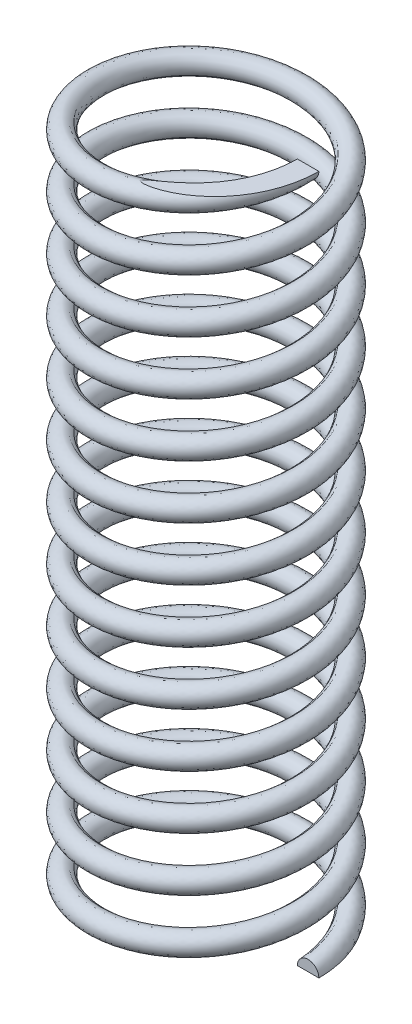
SolidWorks part; units mm, degrees
ref_plane "Front Plane" through (0, 0, 0) normal (0, 0, 1) x (1, 0, 0)
ref_plane "Top Plane" through (0, 0, 0) normal (0, 1, 0) x (1, 0, 0)
ref_plane "Right Plane" through (0, 0, 0) normal (1, 0, 0) x (0, 0, -1)
sketch "Sketch1" plane through (0, 0, 0) normal (0, 1, 0) x (1, 0, 0)
  circle A0 centre (0, 0) radius 19
  dimension "D1" = 38
curve "Helix/Spiral1" pitch 10 height 130 turns 13
sketch "Sketch2" plane through (0, 0, 0) normal (0, 0, 1) x (1, 0, 0)
  line L0 (0, 0) -> (19, 0) construction
  circle A0 centre (19, 0) radius 2
  spline S0 degree 3 poles (19, 0) (19, 0.1719) (18.3234, 0.5183) (15.385, 1.0358) (10.8317, 1.5538) (5.1414, 2.0717) (-1.0886, 2.5896) (-7.2043, 3.1076) (-12.5638, 3.6255) (-16.6045, 4.1434) (-18.9022, 4.6614) (-19.2158, 5.1793) (-17.5122, 5.6972) (-13.9705, 6.2151) (-8.9622, 6.7331) (-3.0132, 7.251) (3.2521, 7.7689) (9.176, 8.2869) (14.1367, 8.8048) (17.6135, 9.3227) (19.2415, 9.8406) (18.8496, 10.3586) (16.4791, 10.8765) (12.3789, 11.3944) (6.9792, 11.9124) (0.8469, 12.4303) (-5.3743, 12.9482) (-11.0313, 13.4661) (-15.5304, 13.9841) (-18.3993, 14.502) (-19.3368, 15.0199) (-18.2445, 15.5378) (-15.2371, 16.0558) (-10.6303, 16.5737) (-4.9076, 17.0916) (1.3302, 17.6096) (7.4284, 18.1275) (12.7469, 18.6454) (16.7273, 19.1633) (18.9518, 19.6813) (19.187, 20.1992) (17.4082, 20.7171) (13.802, 21.2351) (8.747, 21.753) (2.7739, 22.2709) (-3.4904, 22.7888) (-9.3883, 23.3068) (-14.3008, 23.8247) (-17.7121, 24.3426) (-19.2641, 24.8606) (-18.7941, 25.3785) (-16.3512, 25.8964) (-12.1919, 26.4143) (-6.7529, 26.9323) (-0.605, 27.4502) (5.6064, 27.9681) (11.2293, 28.4861) (15.6734, 29.004) (18.4724, 29.5219) (19.3323, 30.0398) (18.1629, 30.5578) (15.0869, 31.0757) (10.4273, 31.5936) (4.6731, 32.1116) (-1.5716, 32.6295) (-7.6513, 33.1474) (-12.9279, 33.6653) (-16.8474, 34.1833) (-18.9985, 34.7012) (-19.1553, 35.2191) (-17.3014, 35.7371) (-13.6314, 36.255) (-8.5305, 36.7729) (-2.5342, 37.2908) (3.7282, 37.8088) (9.5992, 38.3267) (14.4626, 38.8446) (17.8078, 39.3625) (19.2838, 39.8805) (18.7356, 40.3984) (16.2207, 40.9163) (12.0031, 41.4343) (6.5256, 41.9522) (0.363, 42.4701) (-5.8376, 42.988) (-11.4254, 43.506) (-15.814, 44.0239) (-18.5425, 44.5418) (-19.3247, 45.0598) (-18.0783, 45.5777) (-14.9343, 46.0956) (-10.2226, 46.6135) (-4.4379, 47.1315) (1.8127, 47.6494) (7.873, 48.1673) (13.1069, 48.6853) (16.9649, 49.2032) (19.0422, 49.7211) (19.1206, 50.239) (17.1919, 50.757) (13.4587, 51.2749) (8.3126, 51.7928) (2.294, 52.3108) (-3.9654, 52.8287) (-9.8086, 53.3466) (-14.6221, 53.8645) (-17.9008, 54.3825) (-19.3005, 54.9004) (-18.6742, 55.4183) (-16.0876, 55.9363) (-11.8124, 56.4542) (-6.2972, 56.9721) (-0.121, 57.49) (6.0679, 58.008) (11.6198, 58.5259) (15.9521, 59.0438) (18.6098, 59.5618) (19.3141, 60.0797) (17.991, 60.5976) (14.7794, 61.1155) (10.0164, 61.6335) (4.202, 62.1514) (-2.0535, 62.6693) (-8.0934, 63.1873) (-13.2838, 63.7052) (-17.0798, 64.2231) (-19.0829, 64.741) (-19.0829, 65.259) (-17.0798, 65.7769) (-13.2838, 66.2948) (-8.0934, 66.8127) (-2.0535, 67.3307) (4.202, 67.8486) (10.0164, 68.3665) (14.7794, 68.8845) (17.991, 69.4024) (19.3141, 69.9203) (18.6098, 70.4382) (15.9521, 70.9562) (11.6198, 71.4741) (6.0679, 71.992) (-0.121, 72.51) (-6.2972, 73.0279) (-11.8124, 73.5458) (-16.0876, 74.0637) (-18.6742, 74.5817) (-19.3005, 75.0996) (-17.9008, 75.6175) (-14.6221, 76.1355) (-9.8086, 76.6534) (-3.9654, 77.1713) (2.294, 77.6892) (8.3126, 78.2072) (13.4587, 78.7251) (17.1919, 79.243) (19.1206, 79.761) (19.0422, 80.2789) (16.9649, 80.7968) (13.1069, 81.3147) (7.873, 81.8327) (1.8127, 82.3506) (-4.4379, 82.8685) (-10.2226, 83.3865) (-14.9343, 83.9044) (-18.0783, 84.4223) (-19.3247, 84.9402) (-18.5425, 85.4582) (-15.814, 85.9761) (-11.4254, 86.494) (-5.8376, 87.012) (0.363, 87.5299) (6.5256, 88.0478) (12.0031, 88.5657) (16.2207, 89.0837) (18.7356, 89.6016) (19.2838, 90.1195) (17.8078, 90.6375) (14.4626, 91.1554) (9.5992, 91.6733) (3.7282, 92.1912) (-2.5342, 92.7092) (-8.5305, 93.2271) (-13.6314, 93.745) (-17.3014, 94.2629) (-19.1553, 94.7809) (-18.9985, 95.2988) (-16.8474, 95.8167) (-12.9279, 96.3347) (-7.6513, 96.8526) (-1.5716, 97.3705) (4.6731, 97.8884) (10.4273, 98.4064) (15.0869, 98.9243) (18.1629, 99.4422) (19.3323, 99.9602) (18.4724, 100.4781) (15.6734, 100.996) (11.2293, 101.5139) (5.6064, 102.0319) (-0.605, 102.5498) (-6.7529, 103.0677) (-12.1919, 103.5857) (-16.3512, 104.1036) (-18.7941, 104.6215) (-19.2641, 105.1394) (-17.7121, 105.6574) (-14.3008, 106.1753) (-9.3883, 106.6932) (-3.4904, 107.2112) (2.7739, 107.7291) (8.747, 108.247) (13.802, 108.7649) (17.4082, 109.2829) (19.187, 109.8008) (18.9518, 110.3187) (16.7273, 110.8367) (12.7469, 111.3546) (7.4284, 111.8725) (1.3302, 112.3904) (-4.9076, 112.9084) (-10.6303, 113.4263) (-15.2371, 113.9442) (-18.2445, 114.4622) (-19.3368, 114.9801) (-18.3993, 115.498) (-15.5304, 116.0159) (-11.0313, 116.5339) (-5.3743, 117.0518) (0.8469, 117.5697) (6.9792, 118.0876) (12.3789, 118.6056) (16.4791, 119.1235) (18.8496, 119.6414) (19.2415, 120.1594) (17.6135, 120.6773) (14.1367, 121.1952) (9.176, 121.7131) (3.2521, 122.2311) (-3.0132, 122.749) (-8.9622, 123.2669) (-13.9705, 123.7849) (-17.5122, 124.3028) (-19.2158, 124.8207) (-18.9022, 125.3386) (-16.6045, 125.8566) (-12.5638, 126.3745) (-7.2043, 126.8924) (-1.0886, 127.4104) (5.1414, 127.9283) (10.8317, 128.4462) (15.385, 128.9642) (18.3234, 129.4817) (19, 129.8281) (19, 130) knots 0 0 0 0 0.003984 0.007968 0.011952 0.015936 0.01992 0.023904 0.027888 0.031873 0.035857 0.039841 0.043825 0.047809 0.051793 0.055777 0.059761 0.063745 0.067729 0.071713 0.075697 0.079681 0.083665 0.087649 0.091633 0.095618 0.099602 0.103586 0.10757 0.111554 0.115538 0.119522 0.123506 0.12749 0.131474 0.135458 0.139442 0.143426 0.14741 0.151394 0.155378 0.159363 0.163347 0.167331 0.171315 0.175299 0.179283 0.183267 0.187251 0.191235 0.195219 0.199203 0.203187 0.207171 0.211155 0.215139 0.219124 0.223108 0.227092 0.231076 0.23506 0.239044 0.243028 0.247012 0.250996 0.25498 0.258964 0.262948 0.266932 0.270916 0.2749 0.278884 0.282869 0.286853 0.290837 0.294821 0.298805 0.302789 0.306773 0.310757 0.314741 0.318725 0.322709 0.326693 0.330677 0.334661 0.338645 0.342629 0.346614 0.350598 0.354582 0.358566 0.36255 0.366534 0.370518 0.374502 0.378486 0.38247 0.386454 0.390438 0.394422 0.398406 0.40239 0.406375 0.410359 0.414343 0.418327 0.422311 0.426295 0.430279 0.434263 0.438247 0.442231 0.446215 0.450199 0.454183 0.458167 0.462151 0.466135 0.47012 0.474104 0.478088 0.482072 0.486056 0.49004 0.494024 0.498008 0.501992 0.505976 0.50996 0.513944 0.517928 0.521912 0.525896 0.52988 0.533865 0.537849 0.541833 0.545817 0.549801 0.553785 0.557769 0.561753 0.565737 0.569721 0.573705 0.577689 0.581673 0.585657 0.589641 0.593625 0.59761 0.601594 0.605578 0.609562 0.613546 0.61753 0.621514 0.625498 0.629482 0.633466 0.63745 0.641434 0.645418 0.649402 0.653386 0.657371 0.661355 0.665339 0.669323 0.673307 0.677291 0.681275 0.685259 0.689243 0.693227 0.697211 0.701195 0.705179 0.709163 0.713147 0.717131 0.721116 0.7251 0.729084 0.733068 0.737052 0.741036 0.74502 0.749004 0.752988 0.756972 0.760956 0.76494 0.768924 0.772908 0.776892 0.780876 0.784861 0.788845 0.792829 0.796813 0.800797 0.804781 0.808765 0.812749 0.816733 0.820717 0.824701 0.828685 0.832669 0.836653 0.840637 0.844622 0.848606 0.85259 0.856574 0.860558 0.864542 0.868526 0.87251 0.876494 0.880478 0.884462 0.888446 0.89243 0.896414 0.900398 0.904382 0.908367 0.912351 0.916335 0.920319 0.924303 0.928287 0.932271 0.936255 0.940239 0.944223 0.948207 0.952191 0.956175 0.960159 0.964143 0.968127 0.972112 0.976096 0.98008 0.984064 0.988048 0.992032 0.996016 1 1 1 1 construction
  dimension "D1" = 4
sweep "Sweep1" add profiles "Sketch2" path "Helix/Spiral1"
sketch "Sketch3" plane through (0, 0, 0) normal (0, 1, 0) x (1, 0, 0)
  circle A0 centre (0, 0) radius 50
  dimension "D1" = 100
extrude "Cut-Extrude1" cut sketch "Sketch3" against normal up to next
ref_plane "Plane1" through (0, 130, 0) normal (0, 1, 0) x (-1, 0, 0)
sketch "Sketch4" plane through (0, 130, 0) normal (0, 1, 0) x (-1, 0, 0)
  circle A0 centre (0, 0) radius 35
  dimension "D1" = 70
extrude "Cut-Extrude2" cut sketch "Sketch4" along normal up to next
